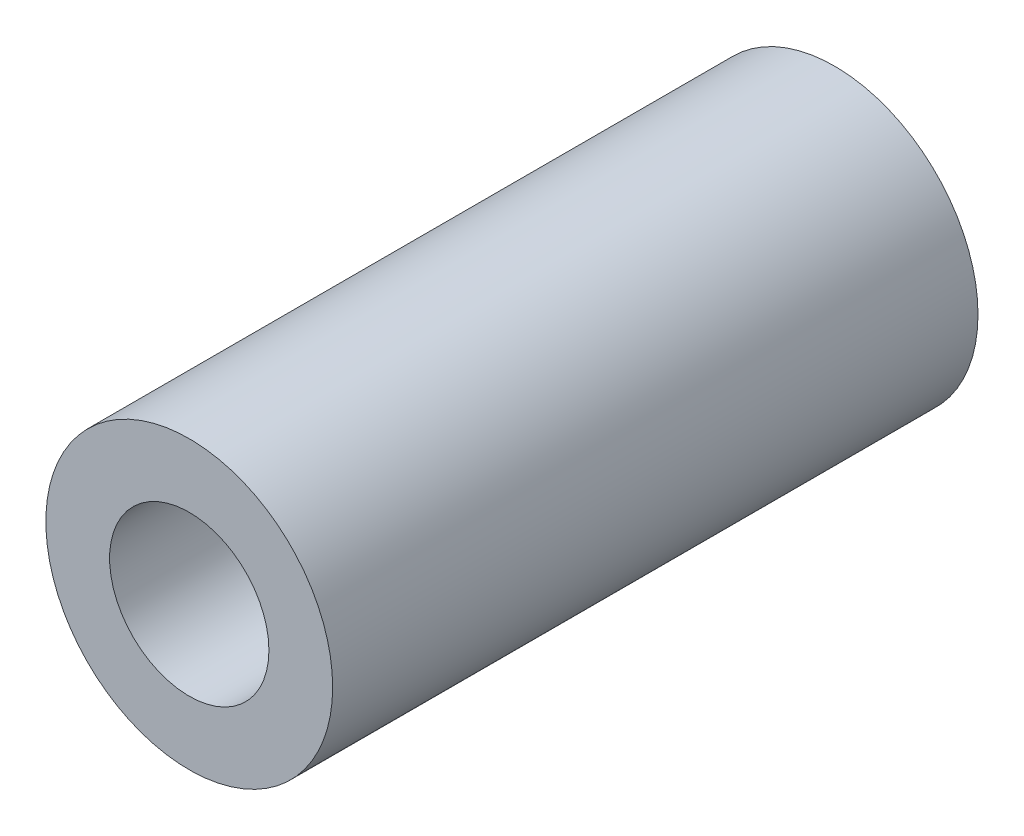
SolidWorks part; units mm, degrees
ref_plane "Front Plane" through (0, 0, 0) normal (0, 0, 1) x (1, 0, 0)
ref_plane "Top Plane" through (0, 0, 0) normal (0, 1, 0) x (1, 0, 0)
ref_plane "Right Plane" through (0, 0, 0) normal (1, 0, 0) x (0, 0, -1)
sketch "Sketch1" plane through (0, 0, 0) normal (0, 0, 1) x (1, 0, 0)
  circle A0 centre (0, 0) radius 9
  circle A1 centre (0, 0) radius 5
  dimension "D1" = 18
  dimension "D2" = 10
extrude "Boss-Extrude1" add sketch "Sketch1" along normal mid plane 40.5
